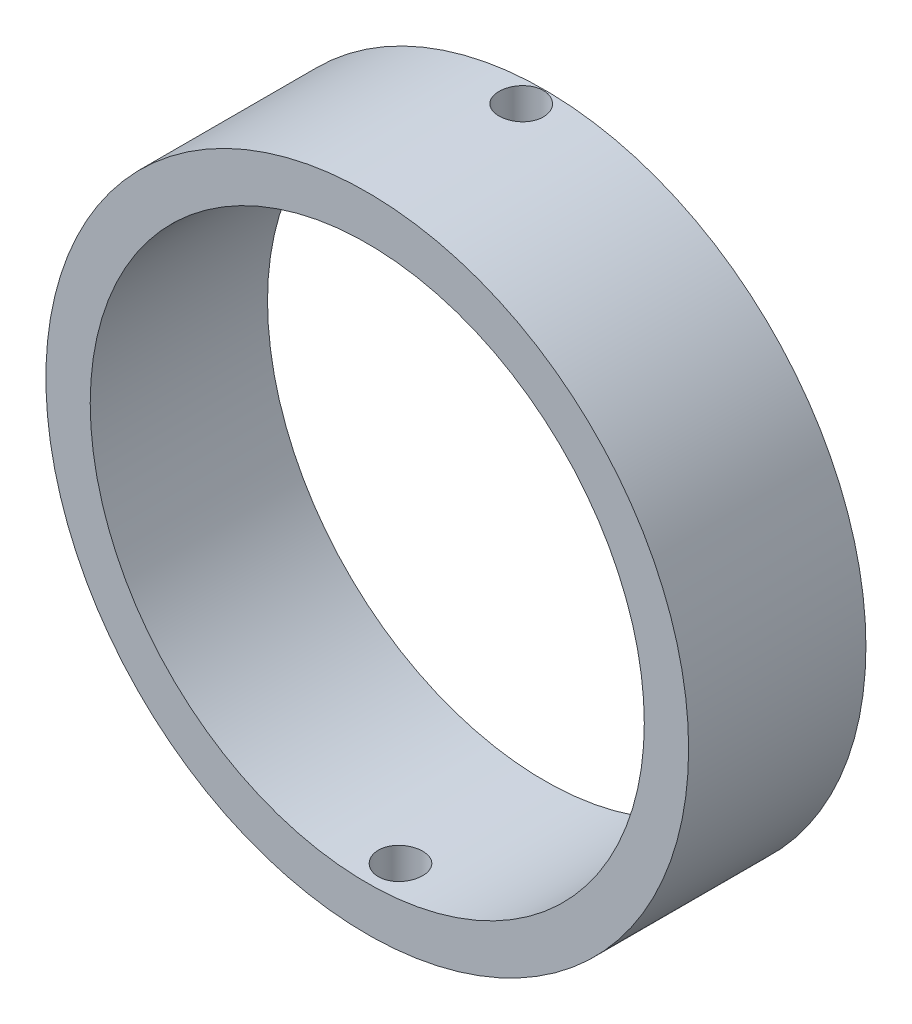
SolidWorks part; units mm, degrees
material "Alumina"
ref_plane "Front Plane" through (0, 0, 0) normal (0, 0, 1) x (1, 0, 0)
ref_plane "Top Plane" through (0, 0, 0) normal (0, 1, 0) x (1, 0, 0)
ref_plane "Right Plane" through (0, 0, 0) normal (1, 0, 0) x (0, 0, -1)
sketch "Sketch1" plane through (0, 0, 0) normal (0, 0, 1) x (1, 0, 0)
  circle A0 centre (0, 0) radius 29
  circle A1 centre (0, 0) radius 25
  dimension "D1" = 58
  dimension "D2" = 50
extrude "Boss-Extrude1" add sketch "Sketch1" along normal blind 16
ref_plane "Plane1" through (0, 29, 0) normal (0, 1, 0) x (1, 0, 0)
ref_plane "Plane2" through (0, -29, 0) normal (0, 1, 0) x (1, 0, 0)
sketch "Sketch3" plane through (0, 29, 0) normal (0, 1, 0) x (1, 0, 0)
  line L0 (0, 0) -> (0, -19.4683) construction
  line L1 (0, -19.4683) -> (0, 6.7745) construction
  circle A0 centre (0, -2.1089) radius 2
  dimension "D1" = 4
extrude "Cut-Extrude1" cut sketch "Sketch3" against normal blind 16
sketch "Sketch4" plane through (0, -29, 0) normal (0, 1, 0) x (1, 0, 0)
  line L0 (0, 0) -> (0, -16) construction
  line L1 (0, -16) -> (0, 12.147) construction
  line L2 (-29, -16) -> (29, -16) construction
  circle A0 centre (0, -13) radius 2
  point P6 (0, 0)
  point P7 (0, -16)
  dimension "D1" = 4
  dimension "D2" = 3
extrude "Cut-Extrude2" cut sketch "Sketch4" along normal blind 16
